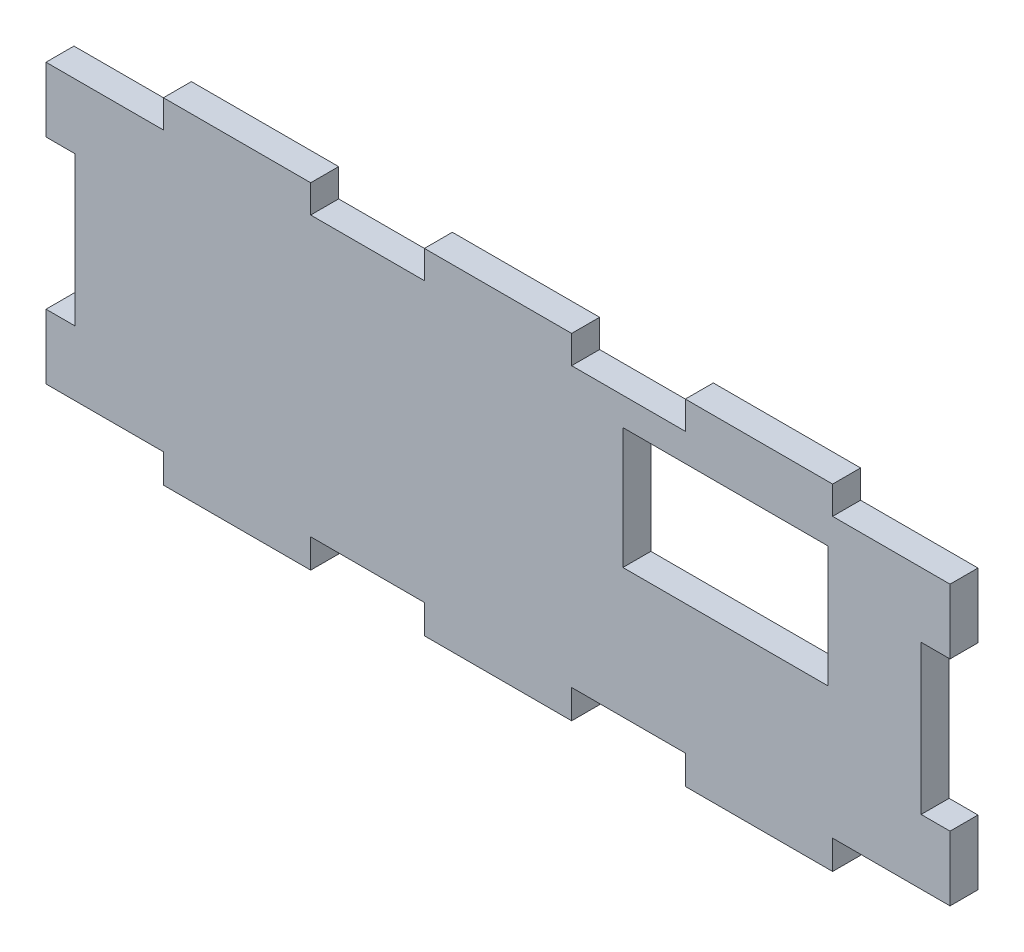
SolidWorks part; units mm, degrees
ref_plane "Front Plane" through (0, 0, 0) normal (0, 0, 1) x (1, 0, 0)
ref_plane "Top Plane" through (0, 0, 0) normal (0, 1, 0) x (1, 0, 0)
ref_plane "Right Plane" through (0, 0, 0) normal (1, 0, 0) x (0, 0, -1)
sketch "Sketch1" plane through (0, 0, 0) normal (0, 0, 1) x (1, 0, 0)
  line L0 (0, 29.9) -> (12.6, 29.9)
  line L1 (12.6, -3.1) -> (28.4, -3.1)
  line L2 (0, 0) -> (0, 6.95)
  line L3 (12.6, 32.9) -> (28.4, 32.9)
  line L4 (97, 0) -> (97, 6.95)
  line L5 (68.6, 32.9) -> (84.4, 32.9)
  line L6 (40.6, 32.9) -> (56.4, 32.9)
  line L7 (12.6, 29.9) -> (12.6, 32.9)
  line L8 (12.6, 32.9) -> (28.4, 32.9)
  line L9 (28.4, 32.9) -> (28.4, 29.9)
  line L10 (28.4, 29.9) -> (40.6, 29.9)
  line L11 (40.6, 29.9) -> (40.6, 32.9)
  line L12 (40.6, 32.9) -> (56.4, 32.9)
  line L13 (56.4, 32.9) -> (56.4, 29.9)
  line L14 (56.4, 29.9) -> (68.6, 29.9)
  line L15 (68.6, 29.9) -> (68.6, 32.9)
  line L16 (68.6, 32.9) -> (84.4, 32.9)
  line L17 (84.4, 32.9) -> (84.4, 29.9)
  line L18 (84.4, 29.9) -> (97, 29.9)
  line L19 (0, 22.95) -> (3.1, 22.95)
  line L20 (3.1, 22.95) -> (3.1, 6.95)
  line L21 (3.1, 6.95) -> (0, 6.95)
  line L22 (0, 0) -> (12.6, 0)
  line L23 (12.6, 0) -> (12.6, -3.1)
  line L24 (12.6, -3.1) -> (28.4, -3.1)
  line L25 (28.4, -3.1) -> (28.4, 0)
  line L26 (28.4, 0) -> (40.6, 0)
  line L27 (40.6, 0) -> (40.6, -3.1)
  line L28 (40.6, -3.1) -> (56.4, -3.1)
  line L29 (56.4, -3.1) -> (56.4, 0)
  line L30 (56.4, 0) -> (68.6, 0)
  line L31 (68.6, 0) -> (68.6, -3.1)
  line L32 (68.6, -3.1) -> (84.4, -3.1)
  line L33 (84.4, -3.1) -> (84.4, 0)
  line L34 (84.4, 0) -> (97, 0)
  line L35 (40.6, -3.1) -> (56.4, -3.1)
  line L36 (68.6, -3.1) -> (84.4, -3.1)
  line L37 (97, 22.95) -> (93.9, 22.95)
  line L38 (93.9, 22.95) -> (93.9, 6.95)
  line L39 (93.9, 6.95) -> (97, 6.95)
  line L40 (0, 22.95) -> (0, 29.9)
  line L41 (97, 22.95) -> (97, 29.9)
  line L43 (61.9, 26.9) -> (83.9, 26.9)
  line L44 (61.9, 26.9) -> (61.9, 13.9)
  line L45 (61.9, 13.9) -> (83.9, 13.9)
  line L46 (83.9, 26.9) -> (83.9, 13.9)
  point P0 (0, 0)
  dimension "D1" = 36
  dimension "D2" = 97
  dimension "D3" = 15.8
  dimension "D4" = 12.2
  dimension "D5" = 3
  dimension "D6" = 16
  dimension "D7" = 3.1
  dimension "D8" = 22
  dimension "D9" = 13
  dimension "D10" = 10
  dimension "D11" = 3
extrude "Boss-Extrude1" add sketch "Sketch1" along normal blind 3 contours L37 L41 L18 L17 L5 L15 L14 L13 L6 L11 L10 L9 L3 L7 L0 L40 L19 L20 L21 L2 L22 L23 L1 L25 L26 L27 L28 L29 L30 L31 L32 L33 L34 L4 L39 L38
